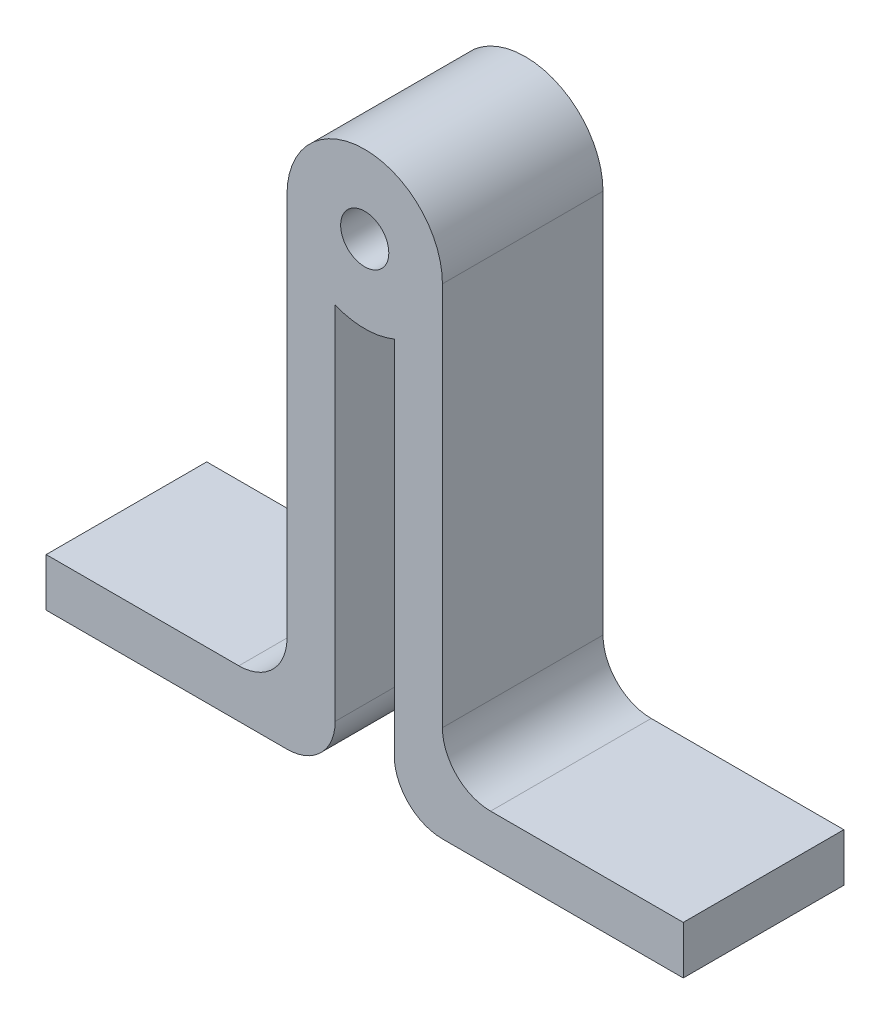
SolidWorks part; units mm, degrees
ref_plane "Front Plane" through (0, 0, 0) normal (0, 0, 1) x (1, 0, 0)
ref_plane "Top Plane" through (0, 0, 0) normal (0, 1, 0) x (1, 0, 0)
ref_plane "Right Plane" through (0, 0, 0) normal (1, 0, 0) x (0, 0, -1)
sketch "Sketch1" plane through (0, 0, 0) normal (0, 0, 1) x (1, 0, 0)
  line L0 (-4.84, 0) -> (-4.84, -23.94)
  line L1 (-7.84, -26.94) -> (-19.84, -26.94)
  line L2 (-19.84, -26.94) -> (-19.84, -29.94)
  line L3 (-19.84, -29.94) -> (-4.84, -29.94)
  line L4 (-1.84, -26.94) -> (-1.84, -4.4766)
  line L5 (0, 0) -> (0, -4.84) construction
  line L6 (1.84, -26.94) -> (1.84, -4.4766)
  line L7 (19.84, -29.94) -> (4.84, -29.94)
  line L8 (19.84, -26.94) -> (19.84, -29.94)
  line L9 (7.84, -26.94) -> (19.84, -26.94)
  line L10 (4.84, 0) -> (4.84, -23.94)
  circle A0 centre (0, 0) radius 1.5
  circle A1 centre (0, 0) radius 4.84
  arc A2 (-1.84, -26.94) -> (-4.84, -29.94) centre (-4.84, -26.94) cw
  arc A3 (-7.84, -26.94) -> (-4.84, -23.94) centre (-7.84, -23.94) ccw
  arc A4 (7.84, -26.94) -> (4.84, -23.94) centre (7.84, -23.94) cw
  arc A5 (1.84, -26.94) -> (4.84, -29.94) centre (4.84, -26.94) ccw
  dimension "D1" = 3
  dimension "D2" = 3.34
  dimension "D5" = 3
  dimension "D3" = 3
  dimension "D4" = 3
  dimension "D6" = 29.94
  dimension "D7" = 15
extrude "Boss-Extrude1" add sketch "Sketch1" along normal blind 10
